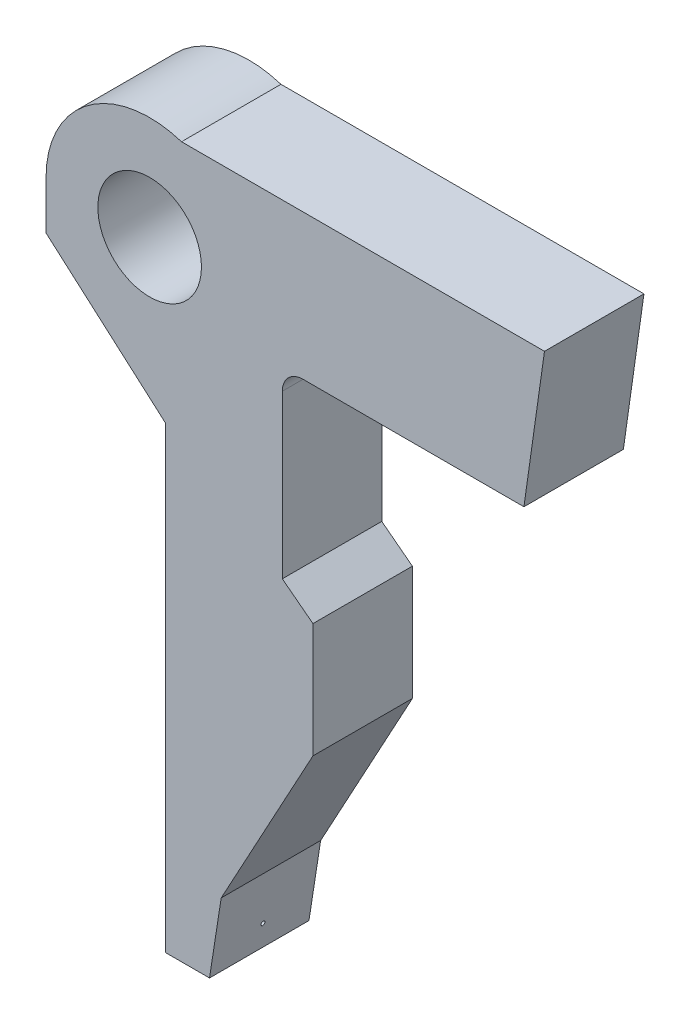
SolidWorks part; units mm, degrees
ref_plane "정면" through (0, 0, 0) normal (0, 0, 1) x (1, 0, 0)
ref_plane "윗면" through (0, 0, 0) normal (0, 1, 0) x (1, 0, 0)
ref_plane "우측면" through (0, 0, 0) normal (1, 0, 0) x (0, 0, -1)
sketch "스케치1" plane through (0, 0, 0) normal (0, 0, 1) x (1, 0, 0)
  line L0 (-5, 0) -> (-5, -2.3265)
  line L1 (0.7542, -29.5199) -> (2.8891, -29.5199)
  line L2 (6.4021, -11.0793) -> (6.4021, -3.2376)
  line L3 (7.4021, -2.2376) -> (18.0636, -2.2376)
  line L4 (18.0636, -2.2376) -> (19.056, 4.758)
  line L5 (2.8891, -29.5199) -> (3.4526, -25.8908)
  line L6 (-5, -2.3265) -> (0.7542, -7.3778)
  line L7 (0.7542, -7.3778) -> (0.7542, -29.5199)
  line L8 (19.056, 4.758) -> (1.5367, 4.758)
  line L9 (3.4526, -25.8908) -> (7.8804, -17.7409)
  line L10 (7.8804, -17.7409) -> (7.8804, -12.2111)
  line L11 (7.8804, -12.2111) -> (6.4021, -11.0793)
  circle A0 centre (0, 0) radius 2.5
  circle A1 centre (0, 0) radius 5
  arc A3 (6.4021, -3.2376) -> (7.4021, -2.2376) centre (7.4021, -3.2376) cw
  dimension "D1" = 5
  dimension "D2" = 10
  dimension "D3" = 1
extrude "보스-돌출1" add sketch "스케치1" along normal blind 4.8
sketch "스케치3" plane through (0.7542, 0, 0) normal (-1, 0, 0) x (0, 0, 1)
  line L0 (4.8, -29.5199) -> (0, -29.5199) construction
  circle A0 centre (2.4, -27.0199) radius 1.825
  point P2 (2.4, -29.5199)
  dimension "D2" = 3.65
  dimension "D1" = 2.5
extrude "컷-돌출1" cut sketch "스케치3" against normal blind 1.8
sketch "스케치4" plane through (2.5542, 0, 0) normal (-1, 0, 0) x (0, 0, 1)
  line L0 (2.4, -25.1949) -> (2.4, -28.8449) construction
  circle A0 centre (2.4, -27.0199) radius 1.825 construction
  circle A1 centre (2.4, -27.0199) radius 1.825 construction
  circle A2 centre (2.4, -28.3449) radius 0.1
  dimension "D1" = 0.5
extrude "컷-돌출2" cut sketch "스케치4" against normal up to next contours A2
